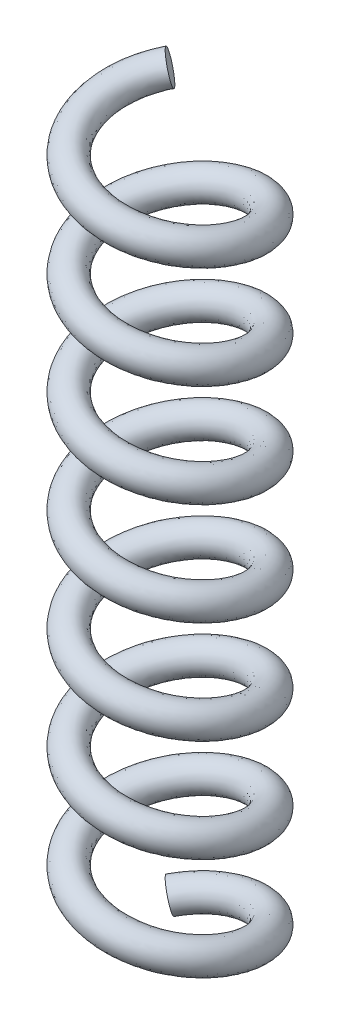
SolidWorks part; units mm, degrees
ref_plane "前视基准面" through (0, 0, 0) normal (0, 0, 1) x (1, 0, 0)
ref_plane "上视基准面" through (0, 0, 0) normal (0, 1, 0) x (1, 0, 0)
ref_plane "右视基准面" through (0, 0, 0) normal (1, 0, 0) x (0, 0, -1)
sketch "草图1" plane through (0, 0, 0) normal (0, 1, 0) x (1, 0, 0)
  circle A0 centre (0, 0) radius 3.5
  dimension "D1" = 7
curve "螺旋线/涡状线1" pitch 5 height 35 turns 7
ref_plane "基准面1" through (-2.4749, 0, -2.4749) normal (0.6895, 0.2217, -0.6895) x (-0.7229, 0.1514, -0.6742)
sketch "草图3" plane through (-2.4749, 0, -2.4749) normal (0.6895, 0.2217, -0.6895) x (-0.7229, 0.1514, -0.6742)
  circle A0 centre (0, 0) radius 0.75
  dimension "D1" = 1.5
sweep "扫描1" add profiles "草图3" path "螺旋线/涡状线1"
sketch "草图4" plane through (0, 0, 0) normal (0, 1, 0) x (1, 0, 0)
  circle A0 centre (0, 0) radius 2.2562
